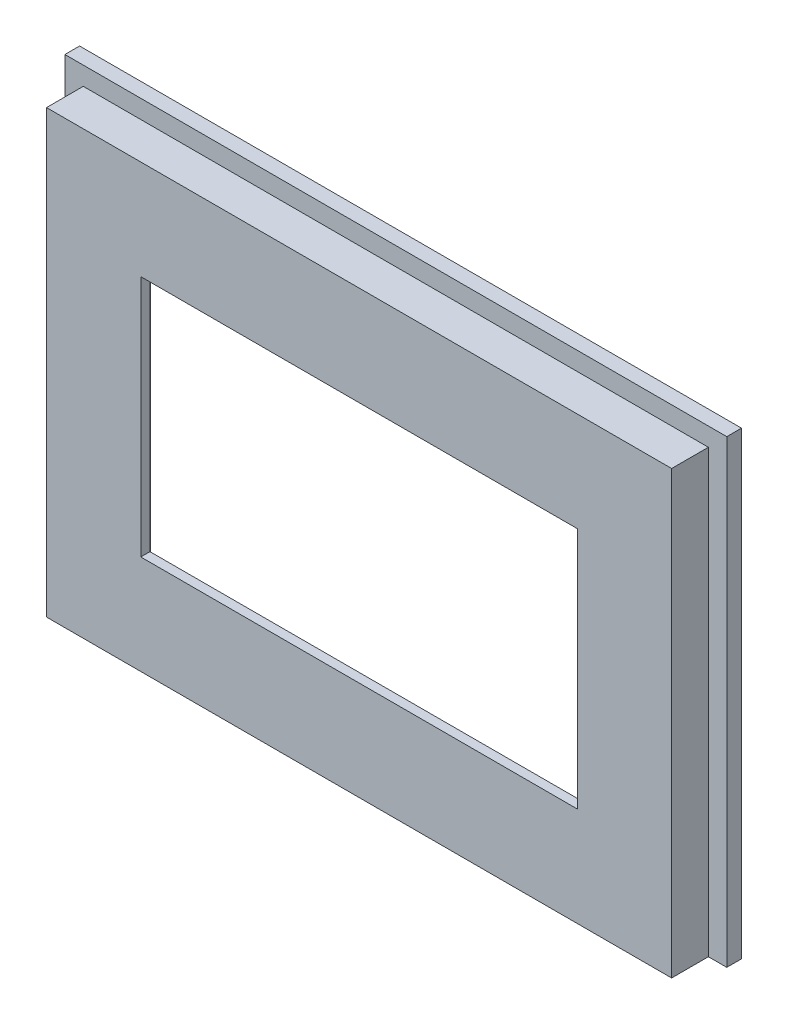
SolidWorks part; units mm, degrees
ref_plane "Front Plane" through (0, 0, 0) normal (0, 0, 1) x (1, 0, 0)
ref_plane "Top Plane" through (0, 0, 0) normal (0, 1, 0) x (1, 0, 0)
ref_plane "Right Plane" through (0, 0, 0) normal (1, 0, 0) x (0, 0, -1)
sketch "Sketch1" plane through (0, 0, 0) normal (0, 0, 1) x (1, 0, 0)
  line L1 (0, 0) -> (-34, 0)
  line L2 (0, 0) -> (0, 24)
  line L3 (0, 24) -> (-34, 24)
  line L4 (-34, 0) -> (-34, 24)
  line L5 (-28.874, 18.6) -> (-5.13, 18.6)
  line L6 (-28.874, 18.6) -> (-28.874, 5.396)
  line L7 (-28.874, 5.396) -> (-5.13, 5.396)
  line L8 (-5.13, 18.6) -> (-5.13, 5.396)
  dimension "D1" = 34
  dimension "D2" = 24
  dimension "D3" = 13.204
  dimension "D4" = 23.744
  dimension "D5" = 5.13
  dimension "D6" = 5.4
extrude "Boss-Extrude1" add sketch "Sketch1" along normal blind 2
sketch "Sketch3" plane through (0, 0, 0) normal (0, 0, -1) x (-1, 0, 0)
  line L0 (5.13, 18.6) -> (28.874, 18.6) construction
  line L1 (3.652, 19.748) -> (30.352, 19.748)
  line L2 (3.652, 19.748) -> (3.652, -2.252)
  line L3 (3.652, -2.252) -> (30.352, -2.252)
  line L4 (30.352, 19.748) -> (30.352, -2.252)
  line L5 (5.13, 5.396) -> (5.13, 18.6) construction
  dimension "D1" = 26.7
  dimension "D2" = 22
  dimension "D3" = 1.148
  dimension "D4" = 1.478
extrude "Cut-Extrude1" cut sketch "Sketch3" against normal blind 1.5
sketch "Sketch4" plane through (0, 0, 0) normal (0, 0, -1) x (-1, 0, 0)
  line L0 (3.652, 0) -> (0, 0) construction
  line L1 (1, 0) -> (-1, 0)
  line L2 (1, 0) -> (1, 23)
  line L3 (0.7391, 25) -> (-1, 25)
  line L4 (-1, 0) -> (-1, 25)
  line L5 (34, 0) -> (30.352, 0) construction
  line L6 (0.7391, 25) -> (35, 25)
  line L7 (34, 24) -> (34, 0) construction
  line L8 (1, 23) -> (33, 23)
  line L9 (35, 25) -> (35, 23.056)
  line L10 (0, 0) -> (0, 24) construction
  line L11 (35, 23.056) -> (35, 0)
  line L12 (35, 0) -> (33, 0)
  line L13 (33, 23) -> (33, 0)
  line L14 (0, 24) -> (34, 24) construction
  dimension "D1" = 2
  dimension "D2" = 2
  dimension "D3" = 2
  dimension "D4" = 1
  dimension "D5" = 1
  dimension "D6" = 1
extrude "Boss-Extrude2" add sketch "Sketch4" along normal blind 0.8
